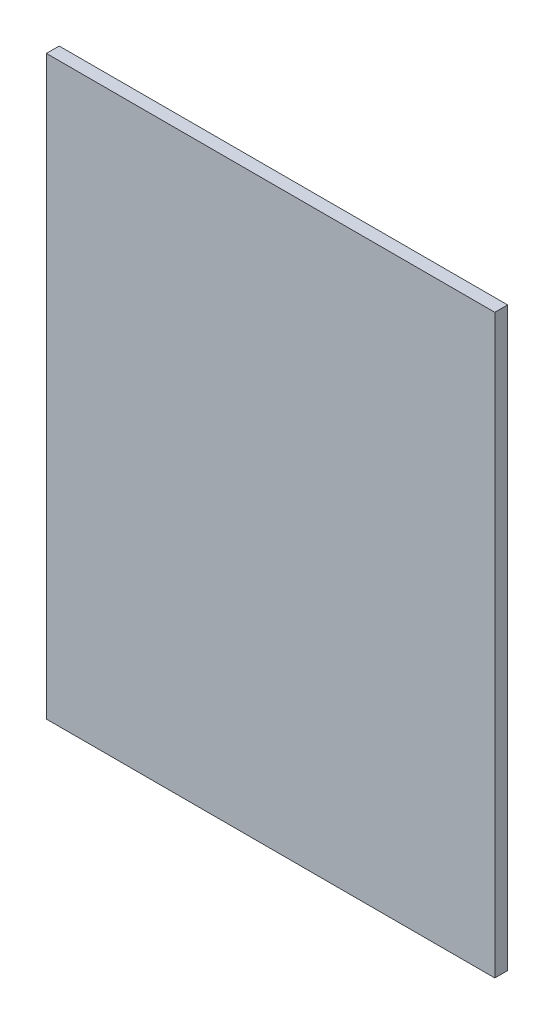
SolidWorks part; units mm, degrees
material "Pine"
ref_plane "Front Plane" through (0, 0, 0) normal (0, 0, 1) x (1, 0, 0)
ref_plane "Top Plane" through (0, 0, 0) normal (0, 1, 0) x (1, 0, 0)
ref_plane "Right Plane" through (0, 0, 0) normal (1, 0, 0) x (0, 0, -1)
sketch "Sketch1" plane through (0, 0, 0) normal (0, 0, 1) x (1, 0, 0)
  line L1 (-70, -90) -> (70, -90)
  line L2 (-70, -90) -> (-70, 90)
  line L3 (-70, 90) -> (70, 90)
  line L4 (70, -90) -> (70, 90)
  line L5 (-70, -90) -> (70, 90) construction
  line L6 (-70, 90) -> (70, -90) construction
  point P0 (0, 0)
  dimension "D1" = 180
  dimension "D2" = 140
extrude "Boss-Extrude1" add sketch "Sketch1" along normal blind 4
